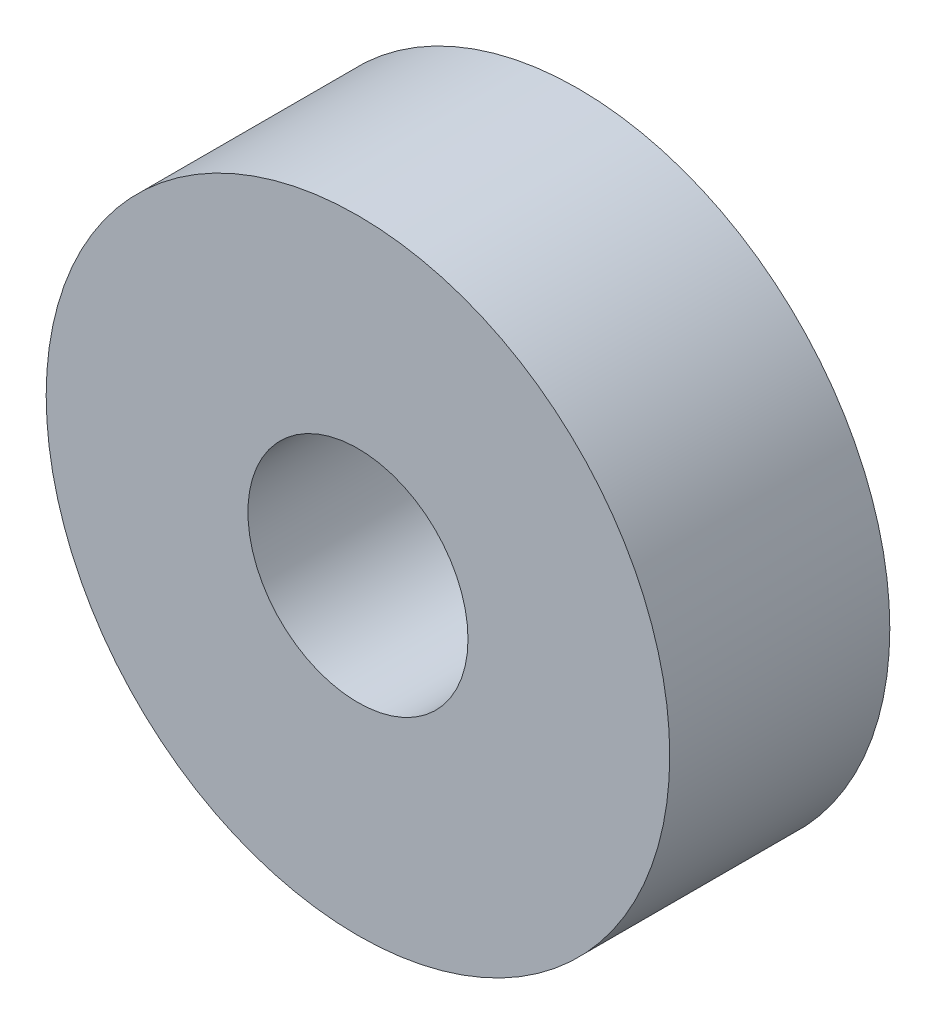
SolidWorks part; units mm, degrees
ref_plane "Front Plane" through (0, 0, 0) normal (0, 0, 1) x (1, 0, 0)
ref_plane "Top Plane" through (0, 0, 0) normal (0, 1, 0) x (1, 0, 0)
ref_plane "Right Plane" through (0, 0, 0) normal (1, 0, 0) x (0, 0, -1)
sketch "Sketch1" plane through (0, 0, 0) normal (0, 0, 1) x (1, 0, 0)
  circle A0 centre (0, 0) radius 8.5
  dimension "D1" = 17
extrude "Boss-Extrude1" add sketch "Sketch1" along normal blind 6
sketch "Sketch2" plane through (0, 0, 6) normal (0, 0, 1) x (1, 0, 0)
  circle A0 centre (0, 0) radius 3
  dimension "D1" = 6
extrude "Cut-Extrude1" cut sketch "Sketch2" against normal through all contours A0
